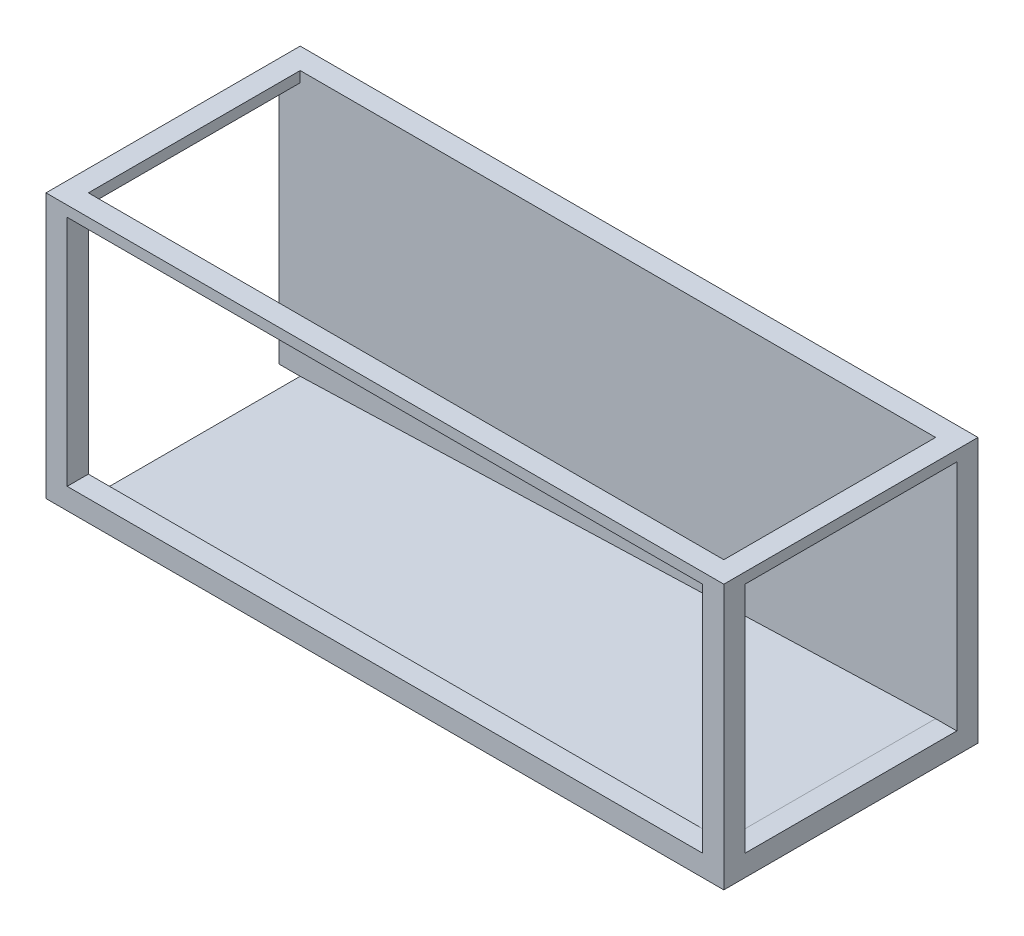
SolidWorks part; units mm, degrees
ref_plane "Front Plane" through (0, 0, 0) normal (0, 0, 1) x (1, 0, 0)
ref_plane "Top Plane" through (0, 0, 0) normal (0, 1, 0) x (1, 0, 0)
ref_plane "Right Plane" through (0, 0, 0) normal (1, 0, 0) x (0, 0, -1)
sketch "Sketch1" plane through (0, 0, 0) normal (0, 1, 0) x (1, 0, 0)
  line L0 (-203.2, 76.2) -> (203.2, 76.2)
  line L1 (-190.5, -63.5) -> (190.5, -63.5)
  line L2 (-190.5, -63.5) -> (-190.5, 63.5)
  line L3 (-190.5, 63.5) -> (190.5, 63.5)
  line L4 (190.5, -63.5) -> (190.5, 63.5)
  line L5 (-190.5, -63.5) -> (190.5, 63.5) construction
  line L6 (-190.5, 63.5) -> (190.5, -63.5) construction
  line L7 (203.2, -76.2) -> (203.2, 76.2)
  line L8 (-203.2, -76.2) -> (203.2, -76.2)
  line L9 (-203.2, -76.2) -> (-203.2, 76.2)
  point P0 (0, 0)
  dimension "D1" = 381
  dimension "D2" = 127
  dimension "D3" = 12.7
extrude "Boss-Extrude1" add sketch "Sketch1" along normal blind 12.7
sketch "Sketch2" plane through (0, 12.7, 0) normal (0, 1, 0) x (1, 0, 0)
  line L1 (-190.5, -63.5) -> (-203.2, -63.5)
  line L2 (-190.5, -63.5) -> (-190.5, -76.2)
  line L3 (-190.5, -76.2) -> (-203.2, -76.2)
  line L4 (-203.2, -63.5) -> (-203.2, -76.2)
  line L8 (-203.2, 76.2) -> (-203.2, -76.2)
  line L9 (-203.2, -76.2) -> (203.2, -76.2)
  line L10 (203.2, -76.2) -> (203.2, 76.2)
  line L11 (203.2, 76.2) -> (-203.2, 76.2)
  line L12 (-203.2, 76.2) -> (-203.2, -76.2)
  line L13 (-203.2, -76.2) -> (203.2, -76.2)
  line L14 (203.2, -76.2) -> (203.2, 76.2)
  line L15 (203.2, 76.2) -> (-203.2, 76.2)
  line M9 (-203.2, 76.2) -> (-203.2, -76.2)
  line M10 (-203.2, -76.2) -> (203.2, -76.2)
  dimension "D1" = 0
extrude "Boss-Extrude2" add sketch "Sketch2" along normal blind 146.05 contours L2 L1 M9 M10
mirror "Mirror1" about plane through (0, 0, 0) normal (1, 0, 0) of "Boss-Extrude2" second plane through (0, 0, 0) second plane normal (0, 0, 1)
sketch "Sketch3" plane through (0, 158.75, 0) normal (0, 1, 0) x (1, 0, 0)
  line L0 (-190.5, -63.5) -> (190.5, -63.5)
  line L1 (-203.2, -76.2) -> (203.2, -76.2)
  line L2 (-203.2, -76.2) -> (-203.2, 76.2)
  line L3 (-203.2, 76.2) -> (203.2, 76.2)
  line L4 (203.2, -76.2) -> (203.2, 76.2)
  line L5 (190.5, -63.5) -> (190.5, 63.5)
  line L6 (-190.5, 63.5) -> (190.5, 63.5)
  line L7 (-190.5, -63.5) -> (-190.5, 63.5)
  dimension "D1" = 12.7
extrude "Boss-Extrude3" add sketch "Sketch3" against normal blind 6.35
sketch "Sketch4" plane through (0, 0, -76.2) normal (0, 0, -1) x (-1, 0, 0)
  line L1 (-203.2, 158.75) -> (203.2, 158.75)
  line L2 (-203.2, 158.75) -> (-203.2, 0)
  line L3 (-203.2, 0) -> (203.2, 0)
  line L4 (203.2, 158.75) -> (203.2, 0)
extrude "Boss-Extrude4" add sketch "Sketch4" against normal up to surface (12.7 mm away)
sketch "Sketch5" plane through (0, 0, -63.5) normal (0, 0, 1) x (1, 0, 0)
  line L0 (190.5, 12.7) -> (-190.5, 0)
  line L1 (-190.5, 0) -> (190.5, 0)
  line L2 (190.5, 0) -> (190.5, 12.7)
sketch "Sketch6" plane through (0, 0, -63.5) normal (0, 0, 1) x (1, 0, 0)
  line L1 (-190.5, 12.7) -> (-203.2, 12.7)
  line L2 (-190.5, 12.7) -> (-190.5, 0)
  line L3 (-190.5, 0) -> (-203.2, 0)
  line L4 (-203.2, 12.7) -> (-203.2, 0)
extrude "Cut-Extrude1" cut sketch "Sketch6" along normal up to surface (127 mm away) up to face at (0, 6.35, 63.5)
extrude "Boss-Extrude6" add sketch "Sketch5" along normal up to surface (127 mm away) up to face at (-67.7333, 55.0333, 63.5)
